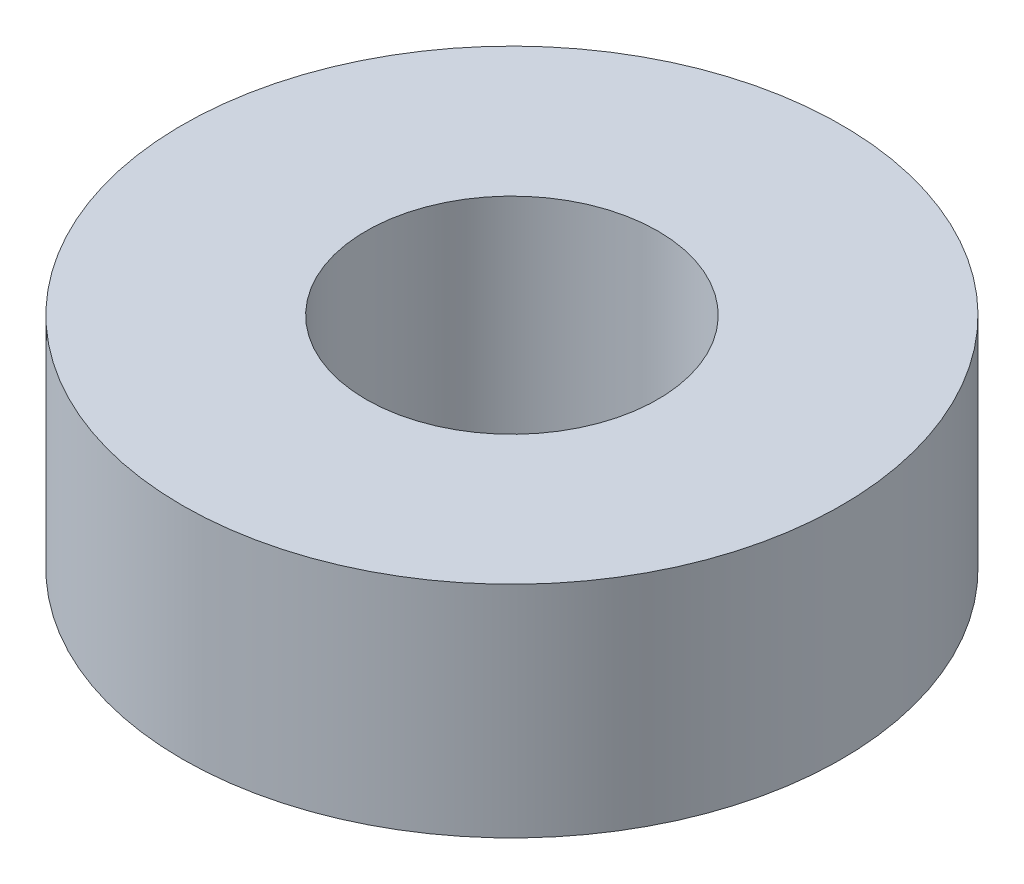
SolidWorks part; units mm, degrees
ref_plane "Front Plane" through (0, 0, 0) normal (0, 0, 1) x (1, 0, 0)
ref_plane "Top Plane" through (0, 0, 0) normal (0, 1, 0) x (1, 0, 0)
ref_plane "Right Plane" through (0, 0, 0) normal (1, 0, 0) x (0, 0, -1)
sketch "Sketch1" plane through (0, 0, 0) normal (0, 1, 0) x (1, 0, 0)
  circle A0 centre (0, 0) radius 2.1082
  circle A1 centre (0, 0) radius 4.7625
  dimension "D1" = 9.525
  dimension "D2" = 4.2164
extrude "Boss-Extrude1" add sketch "Sketch1" along normal blind 3.175
